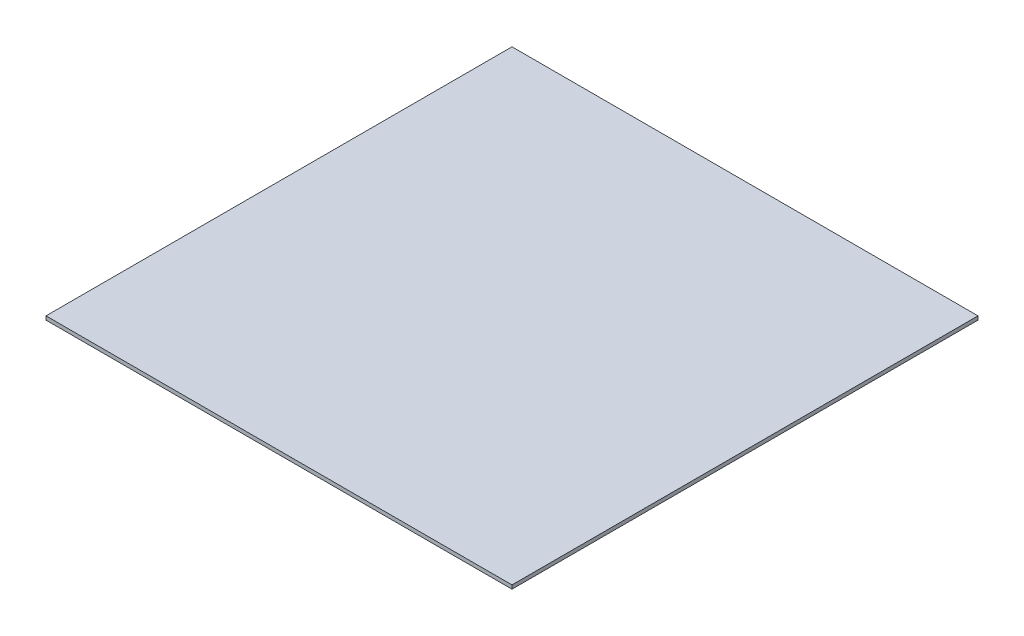
SolidWorks part; units mm, degrees
ref_plane "Plan de face" through (0, 0, 0) normal (0, 0, 1) x (1, 0, 0)
ref_plane "Plan de dessus" through (0, 0, 0) normal (0, 1, 0) x (1, 0, 0)
ref_plane "Plan de droite" through (0, 0, 0) normal (1, 0, 0) x (0, 0, -1)
sketch "Esquisse1" plane through (0, 0, 0) normal (0, 1, 0) x (1, 0, 0)
  line L0 (-100, 100) -> (100, -100) construction
  line L1 (-100, 100) -> (100, 100)
  line L2 (-100, 100) -> (-100, -100)
  line L3 (-100, -100) -> (100, -100)
  line L4 (100, 100) -> (100, -100)
  dimension "D1" = 200
extrude "Boss.-Extru.1" add sketch "Esquisse1" along normal blind 1.6
